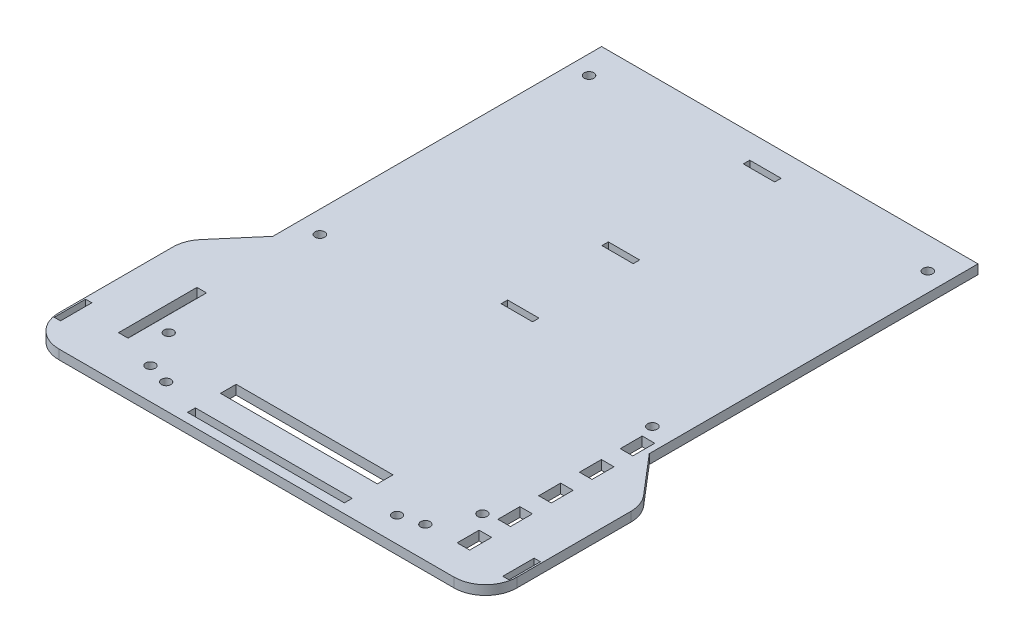
SolidWorks part; units mm, degrees
ref_plane "Front Plane" through (0, 0, 0) normal (0, 0, 1) x (1, 0, 0)
ref_plane "Top Plane" through (0, 0, 0) normal (0, 1, 0) x (1, 0, 0)
ref_plane "Right Plane" through (0, 0, 0) normal (1, 0, 0) x (0, 0, -1)
sketch "Sketch1" plane through (0, 0, 0) normal (0, 1, 0) x (1, 0, 0)
  line L0 (-73, -35) -> (-60, -19.8013)
  line L1 (60, -85) -> (-60, -85)
  line L2 (60, -19.8013) -> (60, 85)
  line L3 (60, 85) -> (-60, 85)
  line L4 (-60, -19.8013) -> (-60, 85)
  line L5 (60, -85) -> (-60, 85) construction
  line L6 (60, 85) -> (-60, -85) construction
  line L7 (0, 0) -> (0, -85) construction
  line L9 (-60, -85) -> (-73, -85)
  line L10 (-73, -35) -> (-73, -85)
  line L11 (60, -85) -> (73, -85)
  line L12 (73, -35) -> (73, -85)
  line L13 (73, -35) -> (60, -19.8013)
  point P0 (0, 0)
  dimension "D1" = 170
  dimension "D2" = 120
  dimension "D3" = 50
  dimension "D4" = 13
  dimension "D5" = 20
extrude "Boss-Extrude1" add sketch "Sketch1" along normal blind 3
sketch "Sketch2" plane through (0, 3, 0) normal (0, 1, 0) x (1, 0, 0)
  line L0 (0, 0) -> (0, 85) construction
  line L1 (60, 85) -> (-60, 85) construction
  line L2 (-60, 85) -> (-60, -19.8013) construction
  circle A0 centre (-53, -11.81) radius 1.525
  circle A1 centre (-54, 75) radius 1.525
  circle A2 centre (53, -11.81) radius 1.525
  circle A3 centre (54, 75) radius 1.525
  dimension "D1" = 10
  dimension "D2" = 3.05
  dimension "D3" = 6
  dimension "D4" = 3.05
  dimension "D5" = 7
  dimension "D6" = 86.81
extrude "Cut-Extrude1" cut sketch "Sketch2" against normal through all
sketch "Sketch3" plane through (0, 3, 0) normal (0, 1, 0) x (1, 0, 0)
  line L0 (-5, 32.14) -> (5, 32.14)
  line L1 (-5, 0.04) -> (5, 0.04)
  line L2 (-5, 0.04) -> (-5, -2.01)
  line L3 (-5, -2.01) -> (5, -2.01)
  line L4 (5, 0.04) -> (5, -2.01)
  line L5 (-5, 0.04) -> (5, -2.01) construction
  line L6 (-5, -2.01) -> (5, 0.04) construction
  line L7 (-5, 32.14) -> (-5, 30.09)
  line L8 (-5, 30.09) -> (5, 30.09)
  line L9 (5, 32.14) -> (5, 30.09)
  line L11 (-5, 77.24) -> (5, 77.24)
  line L12 (-5, 77.24) -> (-5, 75.19)
  line L13 (-5, 75.19) -> (5, 75.19)
  line L14 (-5, 64.24) -> (5, 64.24) [skipped]
  line L15 (-5, 64.24) -> (-5, 62.19) [skipped]
  line L16 (-5, 62.19) -> (5, 62.19) [skipped]
  line L17 (5, 64.24) -> (5, 62.19) [skipped]
  line L18 (5, 77.24) -> (5, 75.19)
  line L19 (-5, 77.24) -> (5, 75.19) construction
  line L20 (-5, 75.19) -> (5, 77.24) construction
  circle A0 centre (-53, -11.81) radius 1.525 construction
  point P0 (0, -0.985)
  point P8 (0, 76.215)
  dimension "D2" = 9.8
  dimension "D1" = 2.05
  dimension "D3" = 10
  dimension "D4" = 0
  dimension "D6" = 2.05
  dimension "D7" = 10
  dimension "D8" = 0
  dimension "D9" = 43.05
  dimension "D10" = 30.05
  dimension "D5" = 3
extrude "Cut-Extrude2" cut sketch "Sketch3" against normal through all
sketch "Sketch4" plane through (0, 3, 0) normal (0, 1, 0) x (1, 0, 0)
  line L0 (-73, -85) -> (73, -85) construction
  line L1 (-60, 85) -> (-60, -19.8013) construction
  line L2 (0, 0) -> (0, -85) construction
  line L4 (-73, -85) -> (73, -85) construction
  circle A1 centre (-50, -63) radius 1.5
  circle A2 centre (-43.8153, -75) radius 1.5
  circle A3 centre (43.8153, -75) radius 1.5
  circle A4 centre (50, -63) radius 1.5
  dimension "D1" = 3
  dimension "D2" = 3
  dimension "D4" = 10
  dimension "D5" = 13.5
  dimension "D6" = 10
  dimension "D3" = 22
extrude "Cut-Extrude3" cut sketch "Sketch4" against normal blind 3
sketch "Sketch5" plane through (0, 3, 0) normal (0, 1, 0) x (1, 0, 0)
  line L0 (0, 0) -> (0, -85) construction
  line L2 (25, -71.5) -> (-25, -71.5)
  line L3 (25, -71.5) -> (25, -66.5)
  line L4 (25, -66.5) -> (-25, -66.5)
  line L5 (-25, -71.5) -> (-25, -66.5)
  line L6 (25, -71.5) -> (-25, -66.5) construction
  line L7 (-73, -85) -> (73, -85) construction
  line L8 (25, -66.5) -> (-25, -71.5) construction
  circle A0 centre (-36.8, -77) radius 1.5
  circle A1 centre (36.8, -77) radius 1.5
  point P0 (0, -69)
  dimension "D3" = 3
  dimension "D4" = 5.5
  dimension "D5" = 8
  dimension "D1" = 5
  dimension "D2" = 50
  dimension "D6" = 36.8
extrude "Cut-Extrude4" cut sketch "Sketch5" against normal blind 3
sketch "Sketch6" plane through (0, 3, 0) normal (0, 1, 0) x (1, 0, 0)
  line L0 (54, -29.0496) -> (54, -36.0496)
  line L5 (25, -71.5) -> (25, -66.5) construction
  line L6 (-25, -71.5) -> (25, -71.5) construction
  line L7 (54, -16.0496) -> (58, -16.0496)
  line L8 (54, -16.0496) -> (54, -23.0496)
  line L9 (54, -23.0496) -> (58, -23.0496)
  line L10 (58, -16.0496) -> (58, -23.0496)
  line L11 (54, -16.0496) -> (58, -23.0496) construction
  line L12 (54, -23.0496) -> (58, -16.0496) construction
  line L13 (54, -29.0496) -> (58, -29.0496)
  line L14 (58, -29.0496) -> (58, -36.0496)
  line L15 (54, -36.0496) -> (58, -36.0496)
  line L16 (54, -42.0496) -> (54, -49.0496)
  line L17 (54, -42.0496) -> (58, -42.0496)
  line L18 (58, -42.0496) -> (58, -49.0496)
  line L19 (54, -49.0496) -> (58, -49.0496)
  line L20 (54, -55.0496) -> (54, -62.0496)
  line L21 (54, -55.0496) -> (58, -55.0496)
  line L22 (58, -55.0496) -> (58, -62.0496)
  line L23 (54, -62.0496) -> (58, -62.0496)
  line L24 (54, -68.0496) -> (54, -75.0496)
  line L25 (54, -68.0496) -> (58, -68.0496)
  line L26 (58, -68.0496) -> (58, -75.0496)
  line L27 (54, -75.0496) -> (58, -75.0496)
  line L35 (0.1365, -44.4032) -> (9.41, -44.4032) construction
  point P0 (-7.793, -44.4032)
  point P30 (-7.793, -44.4032)
  point P55 (-7.793, -44.4032)
  dimension "D1" = 29
  dimension "D2" = 33
  dimension "D3" = 3.4504
  dimension "D4" = 5
  dimension "D5" = 9.4504
  dimension "D6" = 16.4504
  dimension "D7" = 22.4504
  dimension "D8" = 35.4504
  dimension "D9" = 48.4504
extrude "Cut-Extrude5" cut sketch "Sketch6" against normal blind 10
sketch "Sketch7" plane through (0, 3, 0) normal (0, 1, 0) x (1, 0, 0)
  line L0 (-73, -35) -> (-73, -85) construction
  line L1 (54, -45.5496) -> (-47.7588, -45.5496) construction
  line L2 (-73, -85) -> (73, -85) construction
  line L3 (25, -82) -> (-25, -82)
  line L8 (0, -85) -> (0, -22.2641) construction
  line L13 (25, -82) -> (25, -79.5)
  line L14 (25, -79.5) -> (-25, -79.5)
  line L15 (-25, -82) -> (-25, -79.5)
  line L20 (25, -82) -> (-25, -79.5) construction
  line L25 (25, -79.5) -> (-25, -82) construction
  line L26 (54, -42.0496) -> (54, -49.0496) construction
  line L28 (-58, -71) -> (-54.95, -71)
  line L29 (-58, -71) -> (-58, -46)
  line L30 (-58, -46) -> (-54.95, -46)
  line L31 (-54.95, -71) -> (-54.95, -46)
  line L32 (-58, -71) -> (-54.95, -46) construction
  line L33 (-58, -46) -> (-54.95, -71) construction
  circle A0 centre (-68, -57) radius 1.5
  point P10 (0, -80.75)
  point P18 (-56.475, -58.5)
  dimension "D1" = 3
  dimension "D2" = 2.5
  dimension "D3" = 25
  dimension "D7" = 3
  dimension "D10" = 15
  dimension "D8" = 3.05
  dimension "D4" = 50
  dimension "D5" = 5
  dimension "D6" = 28
  dimension "D9" = 14
extrude "Cut-Extrude6" cut sketch "Sketch7" against normal blind 10
fillet "Fillet3" radius 10 4 edges at (-73, 1.5, 35) (73, 1.5, 35) (73, 1.5, 85) (-73, 1.5, 85)
sketch "Sketch8" plane through (0, 3, 0) normal (0, 1, 0) x (1, 0, 0)
  line L0 (73, -75) -> (73, -38.6933) construction
  line L1 (70.5, -77) -> (72.5, -77)
  line L2 (70.5, -77) -> (70.5, -67)
  line L3 (70.5, -67) -> (72.5, -67)
  line L4 (72.5, -77) -> (72.5, -67)
  line L5 (70.5, -77) -> (72.5, -67) construction
  line L6 (70.5, -67) -> (72.5, -77) construction
  line L8 (-63, -85) -> (63, -85) construction
  line L9 (0, -85) -> (0, -22.4512) construction
  line L10 (-70.5, -77) -> (-72.5, -77)
  line L11 (-72.5, -77) -> (-72.5, -67)
  line L12 (-70.5, -67) -> (-72.5, -67)
  line L13 (-70.5, -77) -> (-70.5, -67)
  point P0 (71.5, -72)
  dimension "D1" = 10
  dimension "D2" = 2
  dimension "D3" = 0.5
  dimension "28" = 18
extrude "Cut-Extrude7" cut sketch "Sketch8" against normal blind 10
